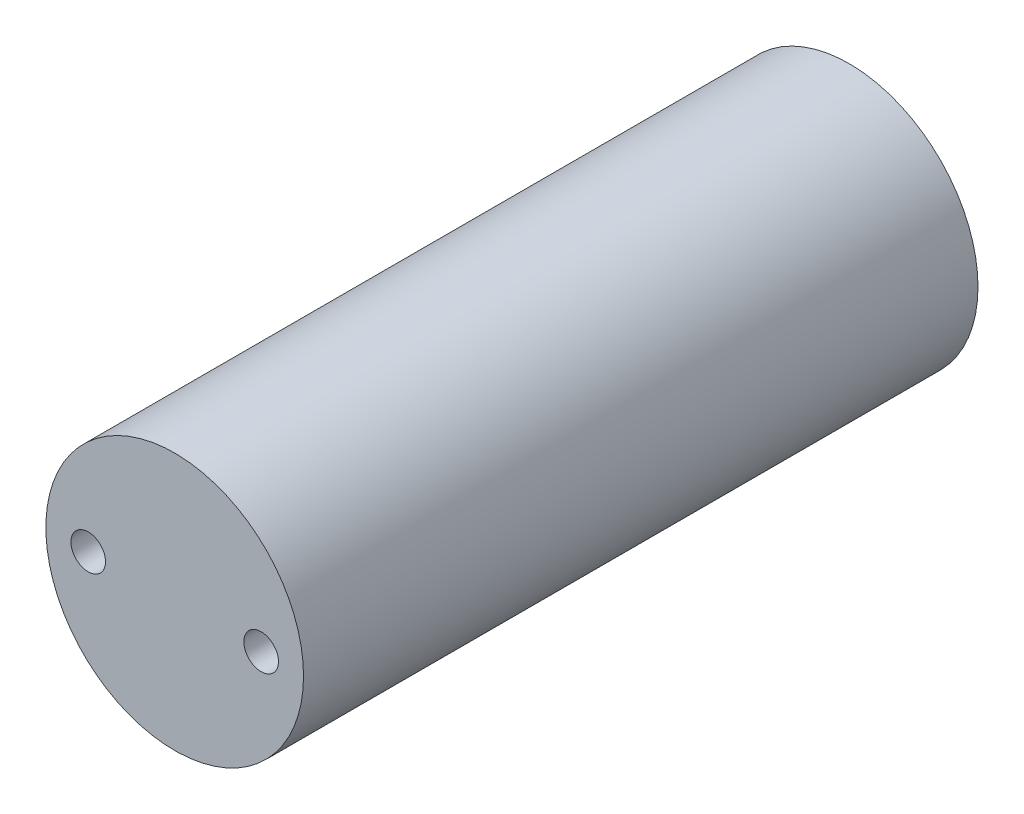
SolidWorks part; units mm, degrees
ref_plane "Front Plane" through (0, 0, 0) normal (0, 0, 1) x (1, 0, 0)
ref_plane "Top Plane" through (0, 0, 0) normal (0, 1, 0) x (1, 0, 0)
ref_plane "Right Plane" through (0, 0, 0) normal (1, 0, 0) x (0, 0, -1)
sketch "Sketch1" plane through (0, 0, 0) normal (0, 0, 1) x (1, 0, 0)
  line L0 (-7.45, 0) -> (7.45, 0) construction
  circle A0 centre (0, 0) radius 7.45
  circle A1 centre (-5, 0) radius 1
  circle A2 centre (5, 0) radius 1
  dimension "D1" = 14.9
  dimension "D2" = 2
  dimension "D3" = 2
  dimension "D4" = 5
  dimension "D5" = 5
extrude "Boss-Extrude1" add sketch "Sketch1" along normal blind 39
